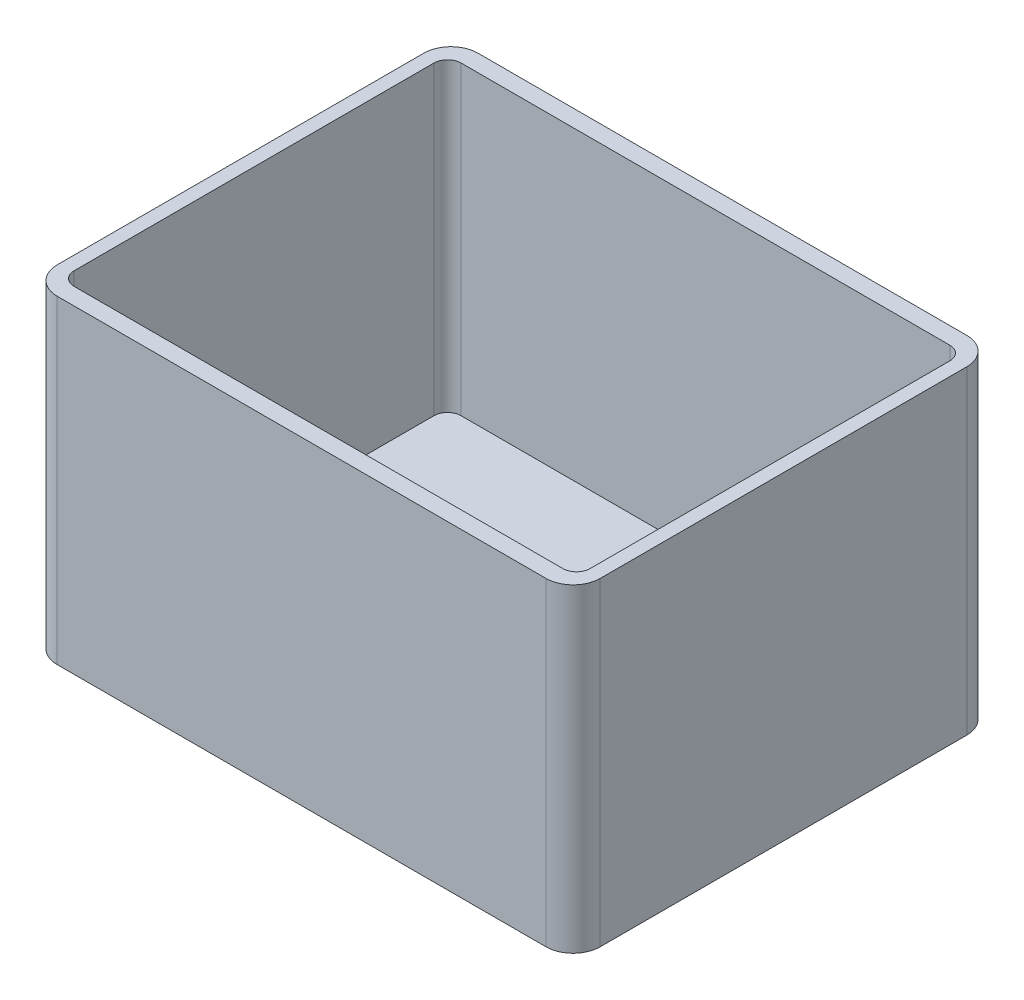
SolidWorks part; units mm, degrees
ref_plane "Front Plane" through (0, 0, 0) normal (0, 0, 1) x (1, 0, 0)
ref_plane "Top Plane" through (0, 0, 0) normal (0, 1, 0) x (1, 0, 0)
ref_plane "Right Plane" through (0, 0, 0) normal (1, 0, 0) x (0, 0, -1)
sketch "Sketch1" plane through (0, 0, 0) normal (0, 1, 0) x (1, 0, 0)
  line L1 (-180, -155) -> (180, -155)
  line L2 (-200, -135) -> (-200, 135)
  line L3 (-180, 155) -> (180, 155)
  line L4 (200, -135) -> (200, 135)
  line L5 (-200, -155) -> (200, 155) construction
  line L6 (-200, 155) -> (200, -155) construction
  arc A0 (-180, -155) -> (-200, -135) centre (-180, -135) cw
  arc A1 (180, -155) -> (200, -135) centre (180, -135) ccw
  arc A2 (180, 155) -> (200, 135) centre (180, 135) cw
  arc A3 (-200, 135) -> (-180, 155) centre (-180, 135) cw
  point P0 (0, 0)
  dimension "D3" = 20
  dimension "D1" = 400
  dimension "D2" = 310
extrude "Boss-Extrude1" add sketch "Sketch1" along normal blind 235
sketch "Sketch2" plane through (0, 235, 0) normal (0, 1, 0) x (1, 0, 0)
  line L1 (-180, -142.5) -> (180, -142.5)
  line L2 (-190, -132.5) -> (-190, 132.5)
  line L3 (-180, 142.5) -> (180, 142.5)
  line L4 (190, -132.5) -> (190, 132.5)
  line L5 (-190, -142.5) -> (190, 142.5) construction
  line L6 (-190, 142.5) -> (190, -142.5) construction
  arc A0 (-180, -142.5) -> (-190, -132.5) centre (-180, -132.5) cw
  arc A1 (180, -142.5) -> (190, -132.5) centre (180, -132.5) ccw
  arc A2 (180, 142.5) -> (190, 132.5) centre (180, 132.5) cw
  arc A3 (-190, 132.5) -> (-180, 142.5) centre (-180, 132.5) cw
  point P0 (0, 0)
  dimension "D3" = 10
  dimension "D1" = 285
  dimension "D2" = 380
extrude "Cut-Extrude1" cut sketch "Sketch2" against normal blind 225
